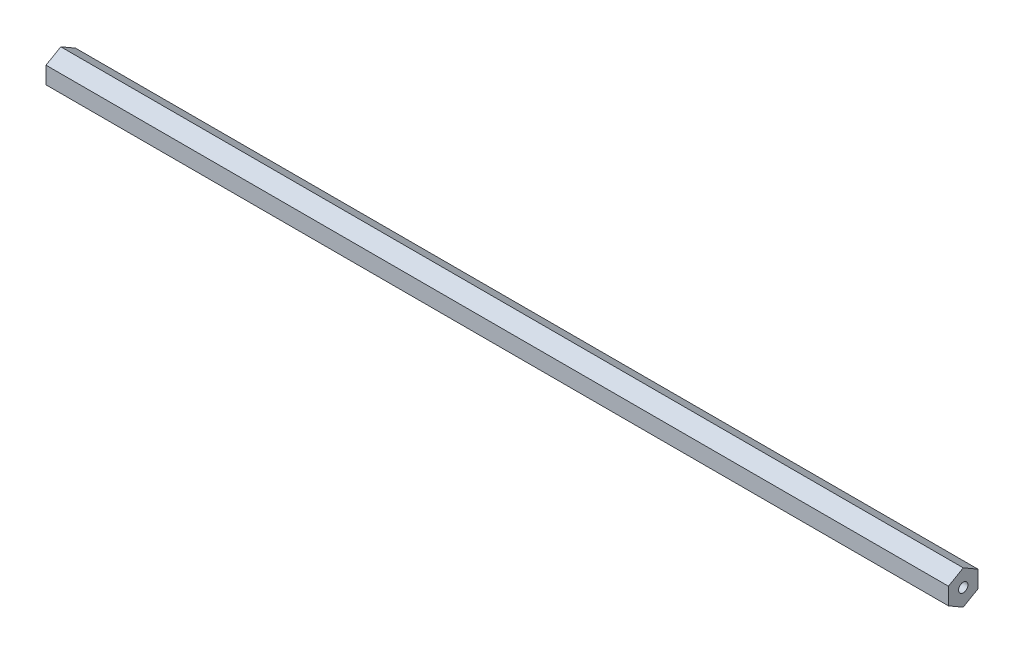
SolidWorks part; units mm, degrees
material "7075-T6 (SN)"
ref_plane "Front Plane" through (0, 0, 0) normal (0, 0, 1) x (1, 0, 0)
ref_plane "Top Plane" through (0, 0, 0) normal (0, 1, 0) x (1, 0, 0)
ref_plane "Right Plane" through (0, 0, 0) normal (1, 0, 0) x (0, 0, -1)
sketch "Sketch1" plane through (0, 0, 0) normal (1, 0, 0) x (0, 0, -1)
  line L1 (0, 7.3323) -> (-6.35, 3.6662)
  line L2 (-6.35, 3.6662) -> (-6.35, -3.6662)
  line L3 (-6.35, -3.6662) -> (0, -7.3323)
  line L4 (0, -7.3323) -> (6.35, -3.6662)
  line L5 (6.35, -3.6662) -> (6.35, 3.6662)
  line L6 (6.35, 3.6662) -> (0, 7.3323)
  circle A2 centre (0, 0) radius 6.35 construction
  dimension "D2" = 12.7
extrude "Boss-Extrude1" add sketch "Sketch1" along normal mid plane 388.1438
hole_wizard "#10-32 Tapped Hole2" positions "3DSketch2" profile "Sketch5" tap size "#10-32" standard "ANSI Inch"
sketch3d "3DSketch2"
  point P0 (194.0719, 0, 0)
  point P12 (-194.0719, 0, 0)
sketch "Sketch5" plane through (194.0719, 0, 0) normal (0, 1, 0) x (0, 0, -1)
  line L0 (0, 0) -> (0, 17.5608)
  line L1 (0, 17.5608) -> (2.0193, 16.3474)
  line L2 (2.0193, 16.3474) -> (2.0193, 0)
  line L5 (2.0193, 0) -> (0, 0)
  line L10 (0, 17.5608) -> (-2.0193, 16.3474) construction
  line L11 (0, -6.35) -> (0, 107.95) construction
  dimension "Tap Drill Dia." = 4.0386
  dimension "Tap Drill Depth" = 16.3474
  dimension "Drill Angle" = 118
cosmetic thread "Hole Thread3" parameters "D1"=13.97, "D2"=4.826
cosmetic thread "Hole Thread4" parameters "D1"=13.97, "D2"=4.826
